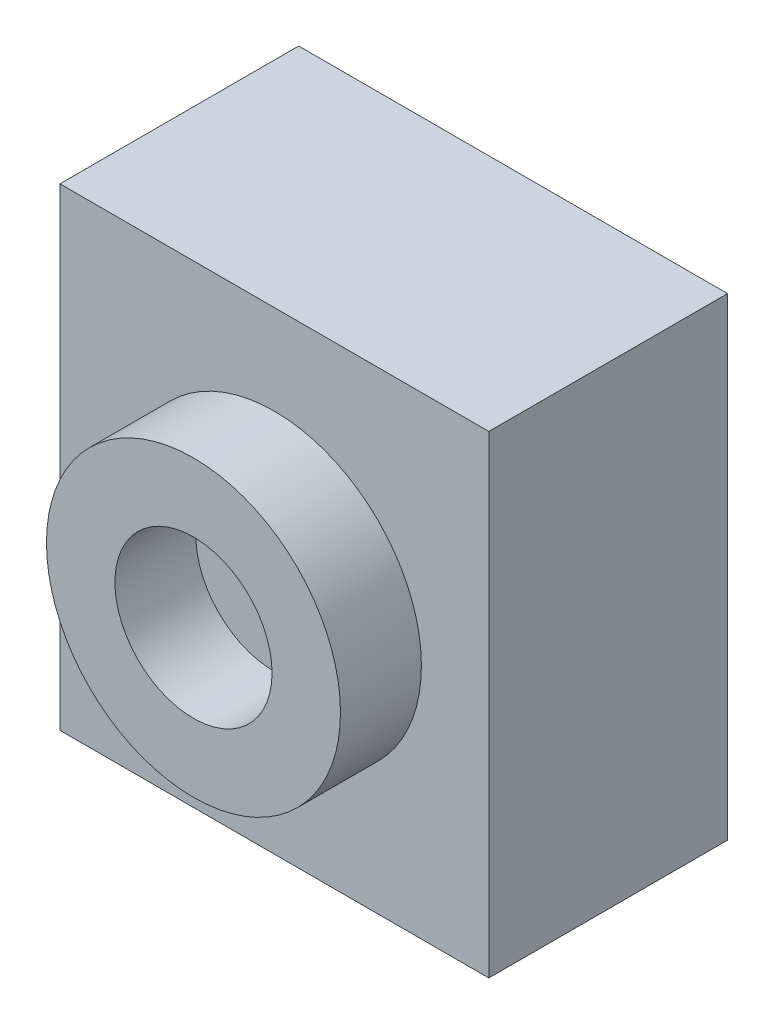
SolidWorks part; units mm, degrees
ref_plane "Plan de face" through (0, 0, 0) normal (0, 0, 1) x (1, 0, 0)
ref_plane "Plan de dessus" through (0, 0, 0) normal (0, 1, 0) x (1, 0, 0)
ref_plane "Plan de droite" through (0, 0, 0) normal (1, 0, 0) x (0, 0, -1)
sketch "Esquisse1" plane through (0, 0, 0) normal (0, 0, 1) x (1, 0, 0)
  line L0 (0, 15.9) -> (0, -19.9769) construction
  line L1 (-5.3, 5.85) -> (5.3, 5.85)
  line L2 (-5.3, 5.85) -> (-5.3, -5.85)
  line L3 (-5.3, -5.85) -> (5.3, -5.85)
  line L4 (5.3, 5.85) -> (5.3, -5.85)
  line L5 (-19.41, 0) -> (25.4362, 0) construction
  dimension "D1" = 10.6
  dimension "D2" = 11.7
extrude "Boss.-Extru.1" add sketch "Esquisse1" along normal blind 5.9
sketch "Esquisse2" plane through (0, 0, 5.9) normal (0, 0, 1) x (1, 0, 0)
  circle A0 centre (0, 0) radius 3.6335
  circle A1 centre (0, 0) radius 1.9418
extrude "Boss.-Extru.2" add sketch "Esquisse2" along normal blind 2
